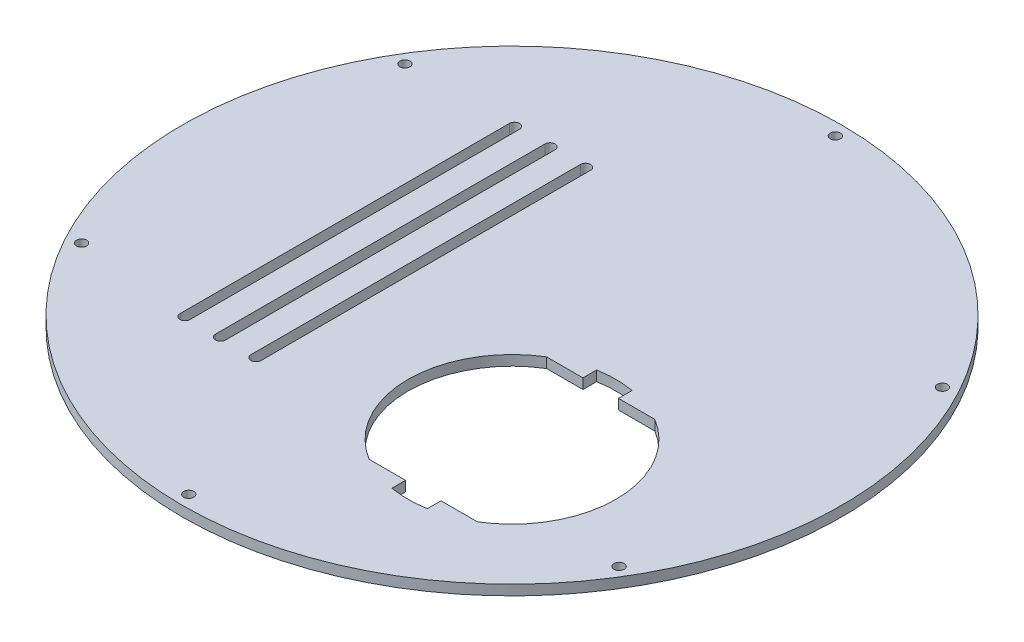
SolidWorks part; units mm, degrees
ref_plane "Plan de face" through (0, 0, 0) normal (0, 0, 1) x (1, 0, 0)
ref_plane "Plan de dessus" through (0, 0, 0) normal (0, 1, 0) x (1, 0, 0)
ref_plane "Plan de droite" through (0, 0, 0) normal (1, 0, 0) x (0, 0, -1)
sketch "Esquisse1" plane through (0, 0, 0) normal (0, 1, 0) x (1, 0, 0)
  circle A0 centre (0, 0) radius 65
extrude "Boss.-Extru.1" add sketch "Esquisse1" along normal blind 2
sketch "Esquisse2" plane through (0, 2, 0) normal (0, 1, 0) x (1, 0, 0)
  circle A2 centre (-53.4759, 32.3509) radius 1
  circle A3 centre (-54.7547, -30.136) radius 1
  circle A4 centre (-1.2788, -62.4869) radius 1
  circle A5 centre (53.4759, -32.3509) radius 1
  circle A6 centre (54.7547, 30.136) radius 1
  circle A7 centre (1.2788, 62.4869) radius 1
extrude "Enlèv. mat.-Extru.1" cut sketch "Esquisse2" against normal blind 3
sketch "Esquisse3" plane through (0, 2, 0) normal (0, 1, 0) x (1, 0, 0)
  circle A0 centre (0, 0) radius 7.5
extrude "Enlèv. mat.-Extru.2" cut sketch "Esquisse3" against normal blind 3
sketch "Esquisse4" plane through (0, 2, 0) normal (0, 1, 0) x (1, 0, 0)
  circle A1 centre (0, 33.5) radius 2
  circle A2 centre (29.0119, 16.75) radius 2
  circle A3 centre (29.0119, -16.75) radius 2
  circle A4 centre (0, -33.5) radius 2
  circle A5 centre (-29.0119, -16.75) radius 2
  circle A6 centre (-29.0119, 16.75) radius 2
extrude "Enlèv. mat.-Extru.4" cut sketch "Esquisse4" against normal blind 4
sketch "Esquisse5" plane through (0, 2, 0) normal (0, 1, 0) x (1, 0, 0)
  circle A0 centre (0, 0) radius 7.5
extrude "Boss.-Extru.3" add sketch "Esquisse5" against normal blind 4
sketch "Esquisse6" plane through (0, 2, 0) normal (0, 1, 0) x (1, 0, 0)
  circle A0 centre (-29.0119, 16.75) radius 2
  circle A1 centre (29.0119, 16.75) radius 2
  circle A2 centre (29.0119, -16.75) radius 2
  circle A3 centre (0, -33.5) radius 2
  circle A4 centre (-29.0119, -16.75) radius 2
  circle A5 centre (0, 33.5) radius 2
extrude "Boss.-Extru.5" add sketch "Esquisse6" against normal blind 2
sketch "Esquisse11" plane through (0, -2, 0) normal (0, -1, 0) x (-1, 0, 0)
  circle A0 centre (0, 0) radius 7.5
extrude "Enlèv. mat.-Extru.7" cut sketch "Esquisse11" against normal blind 2
sketch "Esquisse13" plane through (0, 0, 0) normal (0, -1, 0) x (-1, 0, 0)
  line L0 (-21.2132, -0.7132) -> (-21.2132, -41.7132)
  line L1 (-21.2132, -41.7132) -> (-21.2132, -38.7132)
  line L2 (-21.2132, -41.7132) -> (-21.2132, -38.7132)
  line L3 (-21.2132, -0.7132) -> (-21.2132, -3.7132)
  line L4 (-21.2132, -3.7132) -> (-31.8903, -3.7132)
  line L5 (-21.2132, -3.7132) -> (-10.5361, -3.7132)
  line L6 (-21.2132, -38.7132) -> (-31.8903, -38.7132)
  line L7 (-21.2132, -38.7132) -> (-10.5361, -38.7132)
  line L8 (-21.2132, -38.7132) -> (-24.7132, -38.7132)
  line L9 (-24.7132, -38.7132) -> (-24.7132, -41.4122)
  line L10 (-21.2132, -38.7132) -> (-17.7132, -38.7132)
  line L11 (-17.7132, -38.7132) -> (-17.7132, -41.4122)
  line L12 (-21.2132, -3.7132) -> (-24.7132, -3.7132)
  line L13 (-21.2132, -3.7132) -> (-17.7132, -3.7132)
  line L14 (-17.7132, -3.7132) -> (-17.7132, -1.0142)
  line L15 (-24.7132, -3.7132) -> (-24.7132, -1.0142)
  circle A1 centre (-21.2132, -21.2132) radius 20.5
extrude "Enlèv. mat.-Extru.10" cut sketch "Esquisse13" against normal through all contours L7 A1 L5 L0 | L4 A1 L6 L0 | L0 A1 L15 L4 | L14 A1 L0 L5 | L0 A1 L11 L7 | L9 A1 L0 L6
sketch "Esquisse14" plane through (0, 0, 0) normal (0, -1, 0) x (-1, 0, 0)
  line L8 (32.0031, -32.5) -> (32.0031, -26)
  line L9 (32.0031, -32.5) -> (32.0031, -26)
  line L10 (25, -32.5) -> (25, 32.5) construction
  line L11 (24, -32.5) -> (24, 32.5)
  line L12 (26, -32.5) -> (26, 32.5)
  line L13 (32.0031, -32.5) -> (32.0031, 32.5) construction
  line L14 (31.0031, -32.5) -> (31.0031, 32.5)
  line L15 (33.0031, -32.5) -> (33.0031, 32.5)
  line L16 (17.9969, -32.5) -> (17.9969, 32.5) construction
  line L17 (16.9969, -32.5) -> (16.9969, 32.5)
  line L18 (18.9969, -32.5) -> (18.9969, 32.5)
  arc A0 (24, -32.5) -> (26, -32.5) centre (25, -32.5) ccw
  arc A1 (26, 32.5) -> (24, 32.5) centre (25, 32.5) ccw
  arc A2 (31.0031, -32.5) -> (33.0031, -32.5) centre (32.0031, -32.5) ccw
  arc A3 (33.0031, 32.5) -> (31.0031, 32.5) centre (32.0031, 32.5) ccw
  arc A4 (16.9969, -32.5) -> (18.9969, -32.5) centre (17.9969, -32.5) ccw
  arc A5 (18.9969, 32.5) -> (16.9969, 32.5) centre (17.9969, 32.5) ccw
  point P10 (25, 0)
  point P16 (32.0031, 0)
  point P21 (17.9969, 0)
extrude "Enlèv. mat.-Extru.11" cut sketch "Esquisse14" against normal blind 10
